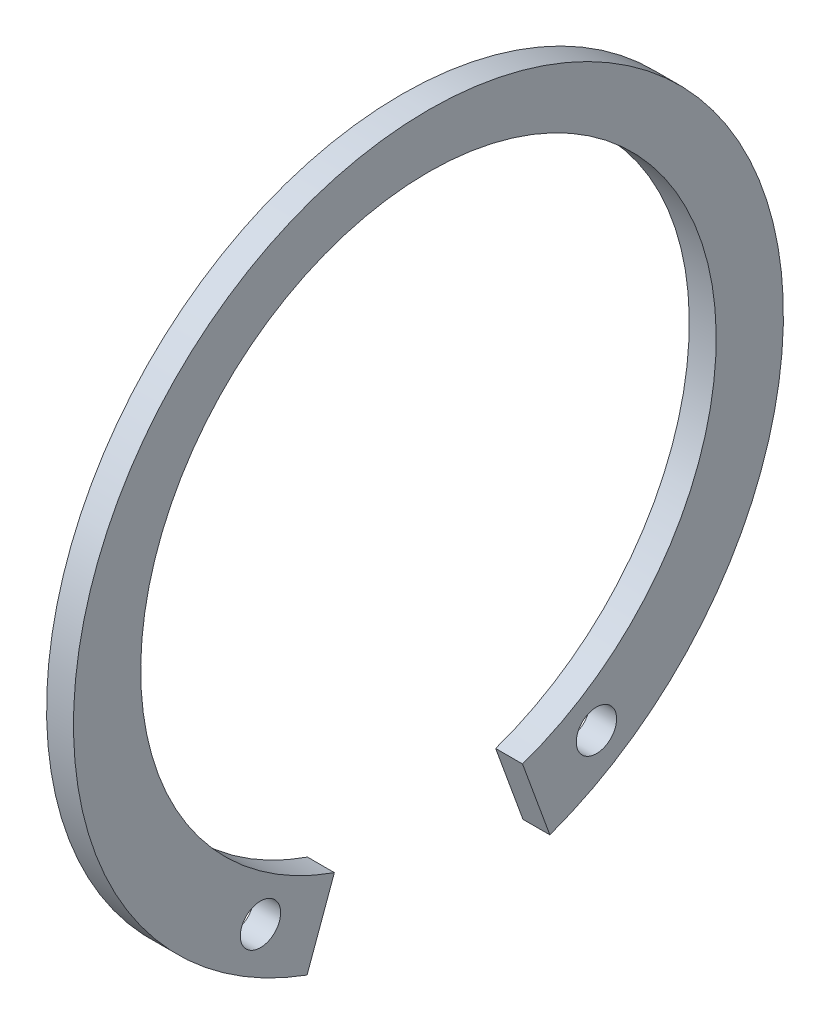
SolidWorks part; units mm, degrees
ref_plane "Płaszczyzna przednia" through (0, 0, 0) normal (0, 0, 1) x (1, 0, 0)
ref_plane "Płaszczyzna górna" through (0, 0, 0) normal (0, 1, 0) x (1, 0, 0)
ref_plane "Płaszczyzna prawa" through (0, 0, 0) normal (1, 0, 0) x (0, 0, -1)
sketch "Szkic2" plane through (0, 0, 0) normal (1, 0, 0) x (0, 0, -1)
  line L1 (-3.4985, -9.6119) -> (-4.5147, -12.4039)
  line L2 (-4.0066, -11.0079) -> (-4.0435, -10.9897)
  line L3 (4.5147, -12.4039) -> (3.4985, -9.6119)
  arc A0 (4.5147, -12.4039) -> (-4.5147, -12.4039) centre (0, 0) ccw
  arc A1 (3.4985, -9.6119) -> (-3.4985, -9.6119) centre (0, 0.5) ccw
  circle A3 centre (-6.2469, -9.9045) radius 0.75
  arc A4 (-4.0435, -10.9897) -> (-4.0051, -11.0038) centre (0, 0) ccw
  circle A5 centre (6.2469, -9.9045) radius 0.75
  dimension "D1" = 26.4
  dimension "D2" = 21.4
  dimension "D5" = 1.5
  dimension "D6" = 1.5
extrude "Dodanie-wyciągnięcie1" add sketch "Szkic2" along normal blind 1 contours L2 A4 L1 A1 L3 A0 A5 A3
